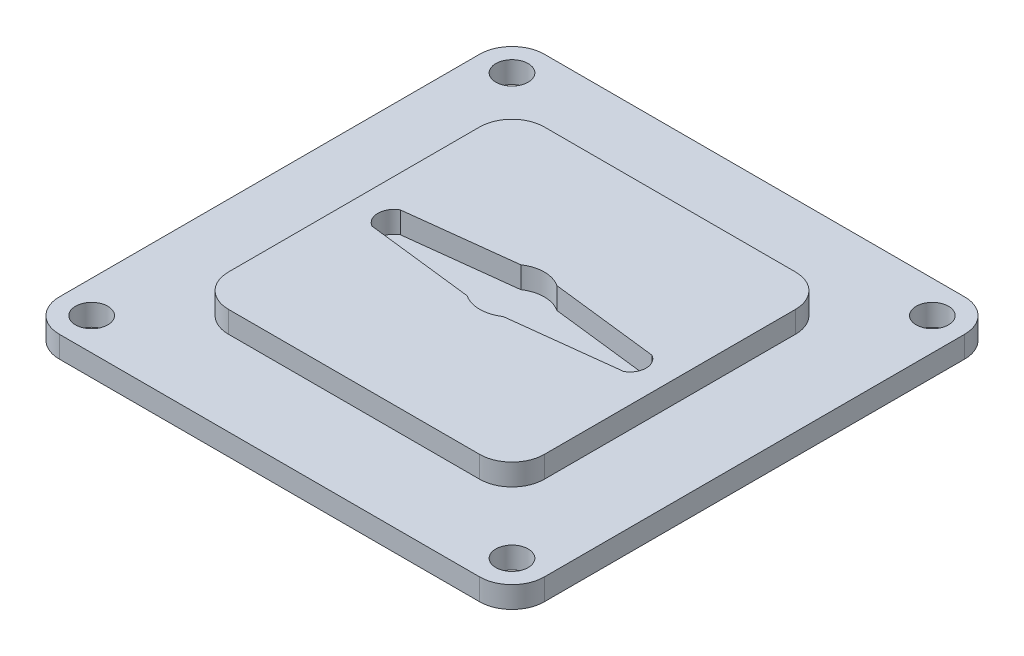
SolidWorks part; units mm, degrees
ref_plane "Ebene vorne" through (0, 0, 0) normal (0, 0, 1) x (1, 0, 0)
ref_plane "Ebene oben" through (0, 0, 0) normal (0, 1, 0) x (1, 0, 0)
ref_plane "Ebene rechts" through (0, 0, 0) normal (1, 0, 0) x (0, 0, -1)
sketch "Sketch2" plane through (0, 0, 0) normal (0, 1, 0) x (1, 0, 0)
  line L1 (-19.5, 22.5) -> (19.5, 22.5)
  line L2 (-22.5, 19.5) -> (-22.5, -19.5)
  line L3 (-19.5, -22.5) -> (19.5, -22.5)
  line L4 (22.5, 19.5) -> (22.5, -19.5)
  line L5 (-22.5, 22.5) -> (22.5, -22.5) construction
  line L6 (-22.5, -22.5) -> (22.5, 22.5) construction
  arc A1 (-22.5, -19.5) -> (-19.5, -22.5) centre (-19.5, -19.5) ccw
  arc A2 (-19.5, 22.5) -> (-22.5, 19.5) centre (-19.5, 19.5) ccw
  arc A3 (19.5, 22.5) -> (22.5, 19.5) centre (19.5, 19.5) cw
  arc A4 (19.5, -22.5) -> (22.5, -19.5) centre (19.5, -19.5) ccw
  circle A5 centre (19.5, -19.5) radius 1.5
  circle A6 centre (19.5, 19.5) radius 1.5
  circle A7 centre (-19.5, 19.5) radius 1.5
  circle A8 centre (-19.5, -19.5) radius 1.5
  point P0 (0, 0)
  dimension "D2" = 3
  dimension "D3" = 3
  dimension "D1" = 45
extrude "Boss-Extrude1" add sketch "Sketch2" along normal blind 2
sketch "Sketch3" plane through (0, 2, 0) normal (0, 1, 0) x (1, 0, 0)
  line L1 (-11.6532, 14.6532) -> (11.6532, 14.6532)
  line L2 (-14.6532, 11.6532) -> (-14.6532, -11.6532)
  line L3 (-11.6532, -14.6532) -> (11.6532, -14.6532)
  line L4 (14.6532, 11.6532) -> (14.6532, -11.6532)
  line L5 (-14.6532, 14.6532) -> (14.6532, -14.6532) construction
  line L6 (-14.6532, -14.6532) -> (14.6532, 14.6532) construction
  arc A0 (-11.6532, 14.6532) -> (-14.6532, 11.6532) centre (-11.6532, 11.6532) ccw
  arc A1 (-14.6532, -11.6532) -> (-11.6532, -14.6532) centre (-11.6532, -11.6532) ccw
  arc A2 (11.6532, 14.6532) -> (14.6532, 11.6532) centre (11.6532, 11.6532) cw
  arc A3 (11.6532, -14.6532) -> (14.6532, -11.6532) centre (11.6532, -11.6532) ccw
  point P0 (0, 0)
  dimension "D1" = 3
extrude "Boss-Extrude2" add sketch "Sketch3" along normal blind 2
sketch "Sketch4" plane through (0, 4, 0) normal (0, 1, 0) x (1, 0, 0)
  line L0 (0, 0) -> (0, -5.6903) construction
  line L1 (-11.7221, 0) -> (12.1575, 0) construction
  line L2 (11.6752, -1.3098) -> (1.6752, -2.4887)
  line L3 (-11.6752, -1.3098) -> (-1.6752, -2.4887)
  line L4 (-11.6752, 1.3098) -> (-1.6752, 2.4887)
  line L5 (11.6752, 1.3098) -> (1.6752, 2.4887)
  arc A0 (-1.6752, -2.4887) -> (1.6752, -2.4887) centre (0, 0) ccw
  arc A1 (-11.6752, 1.3098) -> (-11.6752, -1.3098) centre (-10.9443, 0) ccw
  arc A2 (11.6752, 1.3098) -> (11.6752, -1.3098) centre (10.9443, 0) cw
  arc A3 (-1.6752, 2.4887) -> (1.6752, 2.4887) centre (0, 0) cw
  circle A4 centre (0, 0) radius 3 construction
  point P15 (1.6882, -2.4799)
  point P17 (10.9368, -1.3969)
  point P18 (1.6752, -2.4887)
  dimension "D1" = 6
  dimension "D2" = 1.5
  dimension "D3" = 10
extrude "Cut-Extrude1" cut sketch "Sketch4" against normal blind 2
sketch "Sketch5" plane through (0, 2, 0) normal (0, 1, 0) x (1, 0, 0)
